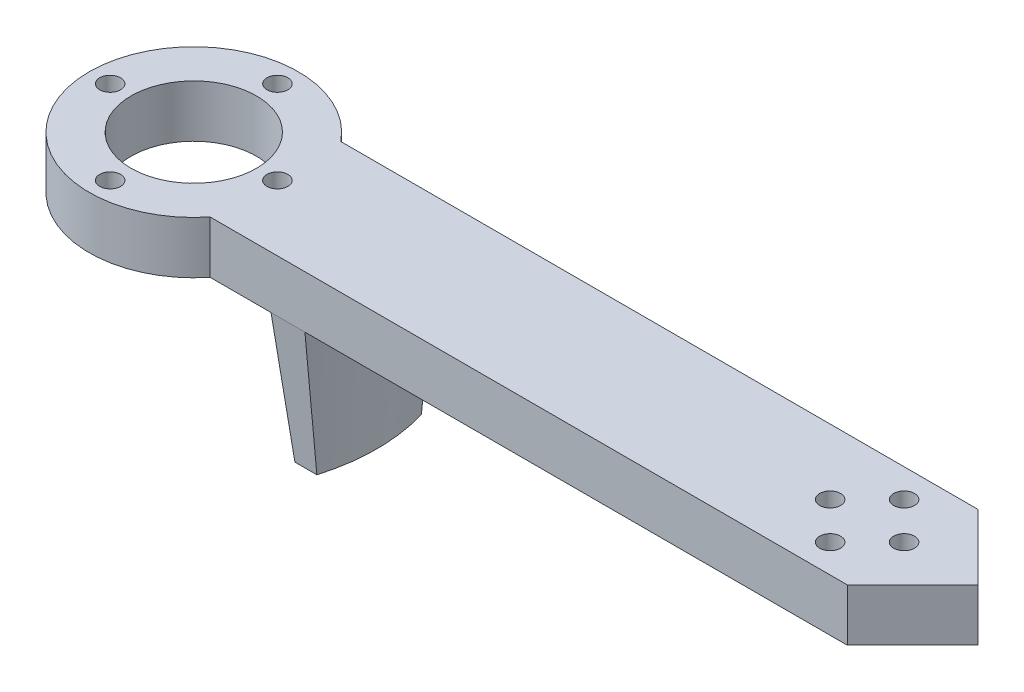
SolidWorks part; units mm, degrees
ref_plane "정면" through (0, 0, 0) normal (0, 0, 1) x (1, 0, 0)
ref_plane "윗면" through (0, 0, 0) normal (0, 1, 0) x (1, 0, 0)
ref_plane "우측면" through (0, 0, 0) normal (1, 0, 0) x (0, 0, -1)
sketch "스케치1" plane through (0, 0, 0) normal (0, 1, 0) x (1, 0, 0)
  line L0 (-75, 0) -> (75, 0) construction
  line L5 (62.5, 12.5) -> (75, 0)
  line L8 (75, 0) -> (62.5, -12.5)
  line L9 (-59.3875, 12.5) -> (62.5, 12.5)
  line L10 (-59.3875, -12.5) -> (62.5, -12.5)
  line L11 (-91, 0) -> (-75, -16) construction
  line L12 (-75, -16) -> (-59, 0) construction
  line L13 (-59, 0) -> (-75, 16) construction
  line L14 (-75, 16) -> (-75, -16) construction
  line L15 (-75, 18) -> (-75, 20) construction
  line L16 (-75, 14) -> (-75, 12)
  circle A0 centre (-75, 0) radius 20
  circle A1 centre (-75, 0) radius 12
  circle A2 centre (-59, 0) radius 2
  circle A3 centre (-91, 0) radius 2
  circle A4 centre (-75, -16) radius 2
  circle A5 centre (-75, 16) radius 2
  dimension "D5" = 4
  dimension "D7" = 8
  dimension "D1" = 45
  dimension "D2" = 45
  dimension "D3" = 25
  dimension "D4" = 150
  dimension "D6" = 32
extrude "보스-돌출1" add sketch "스케치1" along normal blind 10
sketch "스케치2" plane through (0, 0, 0) normal (0, 1, 0) x (1, 0, 0)
  line L0 (75, 0) -> (62.5, -12.5) construction
  line L1 (62.5, 12.5) -> (75, 0) construction
  line L2 (75, 0) -> (62.5, -12.5) construction
  line L3 (62.5, 12.5) -> (75, 0) construction
  line L4 (53.7868, 7.0711) -> (46.7157, 0) construction
  line L5 (53.7868, 7.0711) -> (60.8579, 0) construction
  line L6 (60.8579, 0) -> (53.7868, -7.0711) construction
  line L7 (60.8579, 0) -> (67.9289, 7.0711) construction
  line L8 (60.8579, 0) -> (67.9289, -7.0711) construction
  circle A0 centre (53.7868, 7.0711) radius 2
  circle A1 centre (60.8579, 0) radius 2
  circle A2 centre (46.7157, 0) radius 2
  circle A3 centre (53.7868, -7.0711) radius 2
  dimension "D1" = 4
  dimension "D2" = 10
  dimension "D3" = 10
extrude "컷-돌출1" cut sketch "스케치2" along normal blind 10
sketch "스케치3" plane through (0, 0, 0) normal (0, 1, 0) x (1, 0, 0)
  line L0 (-59.3875, 12.5) -> (62.5, 12.5) construction
  line L1 (-59.3875, 12.5) -> (62.5, 12.5) construction
  line L2 (-59.3875, -12.5) -> (62.5, -12.5) construction
  line L3 (-59.3875, -12.5) -> (62.5, -12.5) construction
  line L4 (-41.2398, 12.5) -> (-47.7282, 12.5)
  line L5 (-47.7282, -12.5) -> (-41.2398, -12.5)
  circle A1 centre (-75, 0) radius 12 construction
  circle A4 centre (-75, 0) radius 12 construction
  arc A5 (-41.2398, -12.5) -> (-41.2398, 12.5) centre (-75, 0) ccw
  arc A6 (-47.7282, -12.5) -> (-47.7282, 12.5) centre (-75, 0) ccw
  point P5 (0, 0)
  point P12 (0, 0)
  dimension "D1" = 60
  dimension "D2" = 72
ref_plane "평면1" through (0, -25, 0) normal (0, 1, 0) x (1, 0, 0)
sketch "스케치4" plane through (0, -25, 0) normal (0, 1, 0) x (1, 0, 0)
  line L0 (-45.6572, -10) -> (-41.459, -10)
  line L1 (-45.6572, 10) -> (-75, 0) construction
  line L2 (-75, 0) -> (-45.6572, -10) construction
  line L3 (-45.6572, 10) -> (-41.459, 10)
  arc A3 (-41.459, -10) -> (-41.459, 10) centre (-75, 0) ccw
  arc A4 (-45.6572, -10) -> (-45.6572, 10) centre (-75, 0) ccw
  point P10 (0, 0)
  dimension "D1" = 62
  dimension "D2" = 70
  dimension "D3" = 20
loft "로프트1" add profiles "스케치3", "스케치4"
